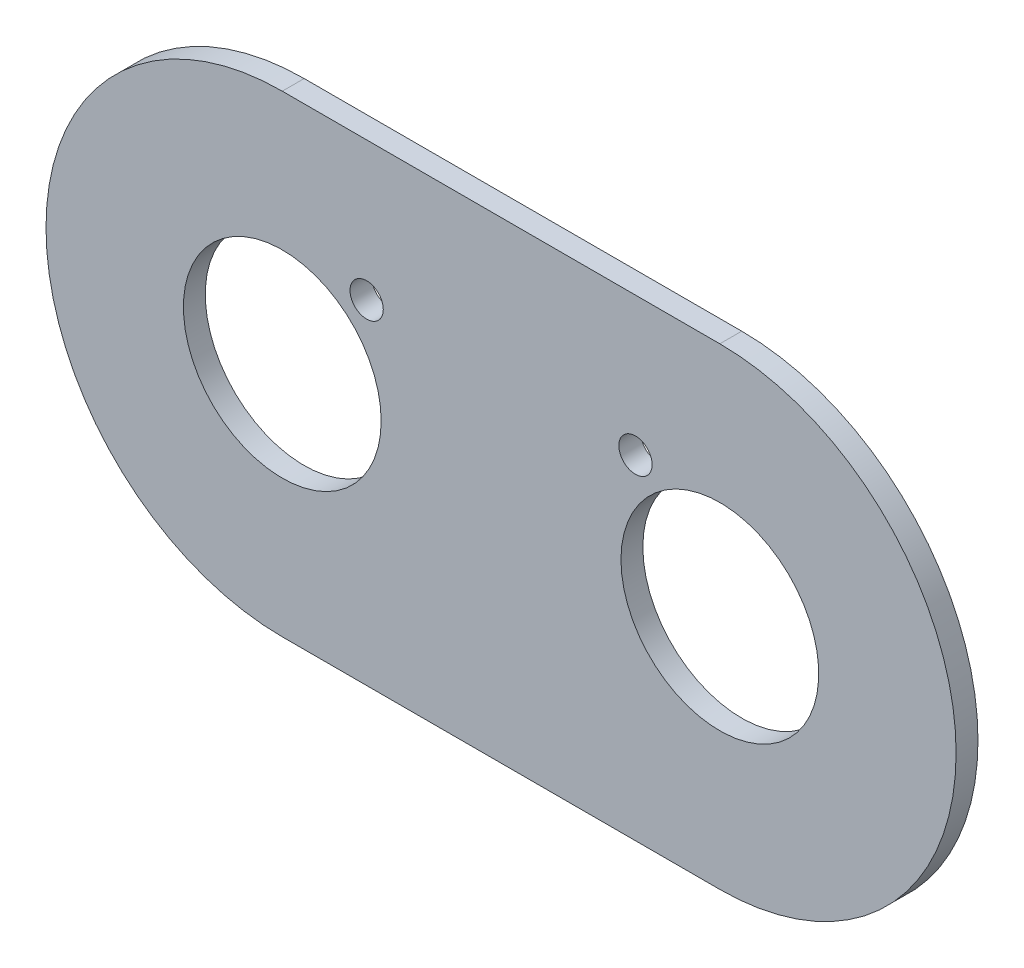
SolidWorks part; units mm, degrees
ref_plane "Front Plane" through (0, 0, 0) normal (0, 0, 1) x (1, 0, 0)
ref_plane "Top Plane" through (0, 0, 0) normal (0, 1, 0) x (1, 0, 0)
ref_plane "Right Plane" through (0, 0, 0) normal (1, 0, 0) x (0, 0, -1)
sketch "Sketch1" plane through (0, 0, 0) normal (0, 0, 1) x (1, 0, 0)
  line L0 (-31.75, 0) -> (31.75, 0) construction
  line L1 (0, -711.9686) -> (0, 34886.4636) construction
  line L2 (-31.75, 34.29) -> (31.75, 34.29)
  line L3 (-31.75, -34.29) -> (31.75, -34.29)
  circle A0 centre (-31.75, 0) radius 14.351
  circle A1 centre (31.75, 0) radius 14.351
  arc A2 (-31.75, 34.29) -> (-31.75, -34.29) centre (-31.75, 0) ccw
  arc A3 (31.75, 34.29) -> (31.75, -34.29) centre (31.75, 0) cw
  circle A4 centre (-19.5064, 14.1775) radius 2.413
  circle A5 centre (-31.75, 0) radius 18.7325 construction
  circle A6 centre (19.5064, 14.1775) radius 2.413
  circle A7 centre (31.75, 0) radius 18.7325 construction
  point P8 (0, 0)
  dimension "D1" = 28.702
  dimension "D3" = 34.29
  dimension "D4" = 4.826
  dimension "D5" = 37.465
  dimension "D2" = 31.75
extrude "Boss-Extrude1" add sketch "Sketch1" along normal blind 3.175
sketch "Sketch2" plane through (0, 0, 3.175) normal (0, 0, 1) x (1, 0, 0)
  line L0 (-1040.2251, -46.99) -> (48959.7749, -46.99) construction
  line L1 (-78.74, -1004.8651) -> (-78.74, 48995.1349) construction
  line L2 (78.74, -1018.9368) -> (78.74, 48981.0632) construction
  line L3 (-31.75, -34.29) -> (31.75, -34.29) construction
  arc A0 (-31.75, 34.29) -> (-31.75, -34.29) centre (-31.75, 0) ccw construction
  arc A1 (31.75, -34.29) -> (31.75, 34.29) centre (31.75, 0) ccw construction
  circle A2 centre (0, 0) radius 3.8644
  circle A3 centre (31.976, 0) radius 1.9642
  circle A4 centre (-31.5605, 0) radius 1.3556
  circle A5 centre (0, 30.2313) radius 1.7457
  circle A6 centre (0, -30.5531) radius 1.6002
  circle A7 centre (60.5095, 0) radius 2.0159
  circle A8 centre (-59.3596, -1.5104) radius 1.1459
  point P5 (-78.74, -46.99)
  point P7 (78.74, -46.99)
  point P11 (-66.04, 0)
  point P17 (66.04, 0)
  point P33 (60.5095, 0)
  point P34 (-59.3596, -1.5104)
  dimension "D1" = 12.7
  dimension "D2" = 12.7
  dimension "D3" = 12.7
